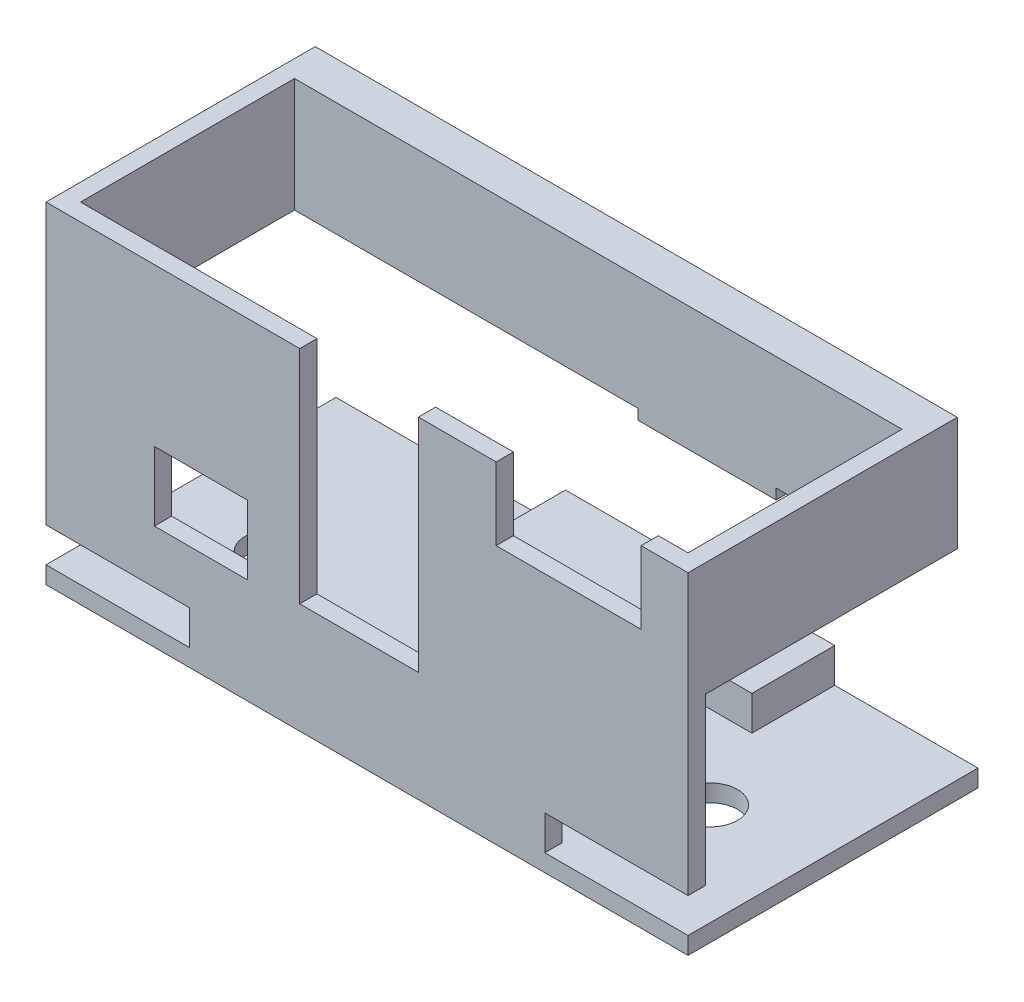
SolidWorks part; units mm, degrees
ref_plane "Front" through (0, 0, 0) normal (0, 0, 1) x (1, 0, 0)
ref_plane "Top" through (0, 0, 0) normal (0, 1, 0) x (1, 0, 0)
ref_plane "Right" through (0, 0, 0) normal (1, 0, 0) x (0, 0, -1)
sketch "Sketch1" plane through (0, 0, 0) normal (0, 0, 1) x (1, 0, 0)
  line L0 (-1.25, 0) -> (-1.25, 24)
  line L1 (-1.25, 0) -> (45.25, 0)
  line L2 (0, 0) -> (0, 22.75) construction
  line L3 (-1.25, 22.75) -> (45.25, 22.75) construction
  line L4 (44, 0) -> (44, 22.75) construction
  line L5 (45.25, 0) -> (45.25, 24)
  line L6 (-1.25, 24) -> (45.25, 24)
  line L7 (-1.25, 0) -> (-1.25, 22.75) construction
  line L8 (45.25, 0) -> (45.25, 22.75) construction
  dimension "D1" = 44
  dimension "D2" = 22.75
  dimension "D5" = 46.5
  dimension "D3" = 1.25
  dimension "D4" = 1.25
  dimension "D6" = 1.25
extrude "Boss-Extrude1" add sketch "Sketch1" against normal blind 21
shell "Shell1" thickness 1.25
sketch "Sketch2" plane through (-1.25, 0, 0) normal (-1, 0, 0) x (0, 0, 1)
  line L0 (-1.25, 24) -> (-1.25, 1.25) construction
  line L1 (-21, 1.25) -> (-1.25, 1.25)
  line L2 (-21, 1.25) -> (-21, 15.75)
  line L3 (-21, 15.75) -> (-1.25, 15.75)
  line L4 (-1.25, 1.25) -> (-1.25, 15.75)
  dimension "D1" = 14.5
extrude "Cut-Extrude1" cut sketch "Sketch2" against normal through all
sketch "Sketch6" plane through (0, 0, 0) normal (0, -1, 0) x (-1, 0, 0)
  line L0 (1.25, 0) -> (-45.25, 0) construction
  line L1 (-22, 0) -> (-22, 5.6918) construction
  circle A0 centre (-37.875, 9) radius 1.95
  circle A1 centre (-6.125, 9) radius 1.95
  dimension "D1" = 3.9
  dimension "D2" = 9
  dimension "D3" = 31.75
extrude "Cut-Extrude4" cut sketch "Sketch6" against normal up to surface (1.25 mm away) contours A1 | A0
sketch "Sketch7" plane through (0, 0, 0) normal (0, 0, 1) x (1, 0, 0)
  line L0 (45.25, 0) -> (45.25, 24) construction
  line L1 (45.25, 1.25) -> (34.875, 1.25)
  line L2 (45.25, 1.25) -> (45.25, 3.75)
  line L3 (45.25, 3.75) -> (34.875, 3.75)
  line L4 (34.875, 1.25) -> (34.875, 3.75)
  line L5 (-1.25, 0) -> (45.25, 0) construction
  line L6 (35.925, 0) -> (39.825, 0) construction
  line L7 (35.925, 0) -> (39.825, 0) construction
  line L8 (37.875, 0) -> (37.875, 1.5787) construction
  line L9 (22, 0) -> (22, 4.652) construction
  line L10 (9.125, 1.25) -> (9.125, 3.75)
  line L11 (-1.25, 3.75) -> (9.125, 3.75)
  line L12 (-1.25, 1.25) -> (-1.25, 3.75)
  line L13 (-1.25, 1.25) -> (9.125, 1.25)
  dimension "D1" = 1.25
  dimension "D2" = 3
  dimension "D3" = 2.5
extrude "Cut-Extrude5" cut sketch "Sketch7" against normal up to surface (1.25 mm away)
sketch "Sketch9" plane through (0, 1.25, 0) normal (0, 1, 0) x (1, 0, 0)
  line L0 (-1.25, 21) -> (45.25, 21) construction
  line L1 (34.875, 21) -> (15.375, 21)
  line L2 (34.875, 21) -> (34.875, 15)
  line L3 (34.875, 15) -> (15.375, 15)
  line L4 (15.375, 21) -> (15.375, 15)
  line L6 (34.875, 1.25) -> (34.875, 21) construction
  dimension "D1" = 6
  dimension "D2" = 19.5
extrude "Boss-Extrude3" add sketch "Sketch9" along normal blind 2.5
sketch "Sketch12" plane through (45.25, 0, 0) normal (1, 0, 0) x (0, 0, -1)
  line L1 (1.25, 15.75) -> (21, 15.75) construction
  line L2 (21, 24) -> (19.5, 24)
  line L3 (21, 24) -> (21, 15.75)
  line L4 (21, 15.75) -> (19.5, 15.75)
  line L5 (19.5, 24) -> (19.5, 15.75)
  dimension "D1" = 1.5
extrude "Cut-Extrude7" cut sketch "Sketch12" along normal through all and the other way through all from surface at -45.25 starting at face at (0, 19.875, -11.125)
sketch "Sketch13" plane through (0, 0, 0) normal (1, 0, 0) x (0, 0, -1)
  line L0 (1.25, 15.75) -> (19.5, 15.75) construction
  line L1 (19.5, 24) -> (16.75, 24)
  line L2 (19.5, 24) -> (19.5, 15.75)
  line L3 (19.5, 15.75) -> (16.75, 15.75)
  line L4 (16.75, 24) -> (16.75, 15.75)
  dimension "D1" = 2.75
extrude "Boss-Extrude4" add sketch "Sketch13" along normal up to vertex (44 mm away) contours L4 L3 L2 L1
sketch "Sketch15" plane through (0, 15.75, 0) normal (0, -1, 0) x (1, 0, 0)
  line L0 (-1.25, -19.5) -> (45.25, -19.5) construction
  line L1 (34.875, -19.5) -> (24.875, -19.5)
  line L2 (34.875, -19.5) -> (34.875, -16.75)
  line L3 (34.875, -16.75) -> (24.875, -16.75)
  line L4 (24.875, -19.5) -> (24.875, -16.75)
  line L5 (44, -16.75) -> (0, -16.75) construction
  line L6 (34.875, -15) -> (34.875, -21) construction
  dimension "D1" = 10
extrude "Boss-Extrude5" add sketch "Sketch15" along normal blind 0.75 contours L1 L4 L3 L2
sketch "Sketch17" plane through (0, 0, -2.75) normal (0, 0, 1) x (1, 0, 0)
  line L4 (8.1, 8.6) -> (11.86, 8.6)
  line L5 (8.1, 11.6) -> (8.1, 8.6)
  line L6 (11.86, 11.6) -> (8.1, 11.6)
  line L7 (11.86, 8.6) -> (11.86, 11.6)
  line L8 (8.1, 8.6) -> (11.86, 8.6)
  line L9 (8.1, 11.6) -> (8.1, 8.6)
  line L10 (11.86, 11.6) -> (8.1, 11.6)
  line L11 (11.86, 8.6) -> (11.86, 11.6)
  line L12 (19.1256, 9.4882) -> (23.7194, 9.4882)
  line L13 (23.7194, 9.4882) -> (23.7194, 14.357)
  line L14 (23.7194, 14.357) -> (19.1256, 14.357)
  line L15 (19.1256, 14.357) -> (19.1256, 9.4882)
  line L16 (19.1256, 9.4882) -> (23.7194, 9.4882)
  line L17 (23.7194, 9.4882) -> (23.7194, 14.357)
  line L18 (23.7194, 14.357) -> (19.1256, 14.357)
  line L19 (19.1256, 14.357) -> (19.1256, 9.4882)
  dimension "D1" = 0
  dimension "D2" = 0
sketch "Sketch18" plane through (0, 0, 0) normal (0, 0, 1) x (1, 0, 0)
  line L0 (8.1, 11.6) -> (8.1, 8.6) construction
  line L1 (6.6, 12.6) -> (13.36, 12.6)
  line L2 (6.6, 12.6) -> (6.6, 7.6)
  line L3 (6.6, 7.6) -> (13.36, 7.6)
  line L4 (13.36, 12.6) -> (13.36, 7.6)
  line L5 (11.86, 11.6) -> (8.1, 11.6) construction
  line L6 (11.86, 8.6) -> (11.86, 11.6) construction
  line L7 (8.1, 8.6) -> (11.86, 8.6) construction
  dimension "D1" = 1.5
  dimension "D2" = 1
  dimension "D3" = 1.5
  dimension "D4" = 1
extrude "Cut-Extrude8" cut sketch "Sketch18" against normal up to next
sketch "Sketch22" plane through (0, 0, 0) normal (0, 0, 1) x (1, 0, 0)
  line L0 (45.25, 24) -> (-1.25, 24) construction
  line L1 (17.1256, 24) -> (25.7194, 24)
  line L2 (17.1256, 24) -> (17.1256, 7.9882)
  line L3 (17.1256, 7.9882) -> (25.7194, 7.9882)
  line L4 (25.7194, 24) -> (25.7194, 7.9882)
  line L5 (19.1256, 14.357) -> (19.1256, 9.4882) construction
  line L6 (23.7194, 9.4882) -> (23.7194, 14.357) construction
  line L7 (19.1256, 9.4882) -> (23.7194, 9.4882) construction
  dimension "D1" = 2
  dimension "D2" = 2
  dimension "D3" = 1.5
extrude "Cut-Extrude9" cut sketch "Sketch22" against normal up to next
ref_plane "Plane1" through (41.175, 19.5, -0.25) normal (1, 0, 0) x (0, -1, 0)
sketch "Sketch25" plane through (0, 0, 0) normal (0, 0, 1) x (1, 0, 0)
  line L1 (41.85, 18.75) -> (31.35, 18.75)
  line L2 (41.85, 18.75) -> (41.85, 24)
  line L3 (41.85, 24) -> (31.35, 24)
  line L4 (31.35, 18.75) -> (31.35, 24)
  line L16 (17.1256, 7.9882) -> (17.1256, 24)
  line L17 (17.1256, 24) -> (-1.25, 24)
  line L18 (-1.25, 24) -> (-1.25, 3.75)
  line L19 (-1.25, 3.75) -> (9.125, 3.75)
  line L20 (9.125, 3.75) -> (9.125, 1.25)
  line L21 (9.125, 1.25) -> (-1.25, 1.25)
  line L22 (-1.25, 1.25) -> (-1.25, 0)
  line L23 (-1.25, 0) -> (45.25, 0)
  line L24 (45.25, 0) -> (45.25, 1.25)
  line L25 (45.25, 1.25) -> (34.875, 1.25)
  line L26 (34.875, 1.25) -> (34.875, 3.75)
  line L27 (34.875, 3.75) -> (45.25, 3.75)
  line L28 (45.25, 3.75) -> (45.25, 24)
  line L29 (45.25, 24) -> (25.7194, 24)
  line L30 (25.7194, 24) -> (25.7194, 7.9882)
  line L31 (25.7194, 7.9882) -> (17.1256, 7.9882)
  line L32 (17.1256, 7.9882) -> (17.1256, 24)
  line L33 (17.1256, 24) -> (-1.25, 24)
  line L34 (-1.25, 24) -> (-1.25, 3.75)
  line L35 (-1.25, 3.75) -> (9.125, 3.75)
  line L36 (9.125, 3.75) -> (9.125, 1.25)
  line L37 (9.125, 1.25) -> (-1.25, 1.25)
  line L38 (-1.25, 1.25) -> (-1.25, 0)
  line L39 (-1.25, 0) -> (45.25, 0)
  line L40 (45.25, 0) -> (45.25, 1.25)
  line L41 (45.25, 1.25) -> (34.875, 1.25)
  line L42 (34.875, 1.25) -> (34.875, 3.75)
  line L43 (34.875, 3.75) -> (45.25, 3.75)
  line L44 (45.25, 3.75) -> (45.25, 24)
  line L45 (45.25, 24) -> (25.7194, 24)
  line L46 (25.7194, 24) -> (25.7194, 7.9882)
  line L47 (25.7194, 7.9882) -> (17.1256, 7.9882)
  line L52 (31.6, 24) -> (31.6, 19.5)
  line L53 (31.6, 19.5) -> (41.6, 19.5)
  line L54 (41.6, 19.5) -> (41.6, 24)
  line L55 (41.6, 24) -> (31.6, 24)
  line L56 (31.6, 24) -> (31.6, 19.5)
  line L57 (31.6, 19.5) -> (41.6, 19.5)
  line L58 (41.6, 19.5) -> (41.6, 24)
  line L59 (41.6, 24) -> (31.6, 24)
  line M34 (45.25, 24) -> (25.7194, 24)
  dimension "D3" = 0.25
  dimension "D4" = 0.75
  dimension "D5" = 0.25
  dimension "D1" = 0
  dimension "D2" = 0
extrude "Cut-Extrude15" cut sketch "Sketch25" against normal up to next contours L58 L57 L56 L45 L4 L1 L2 M34 | L57 L58 L45 L56
